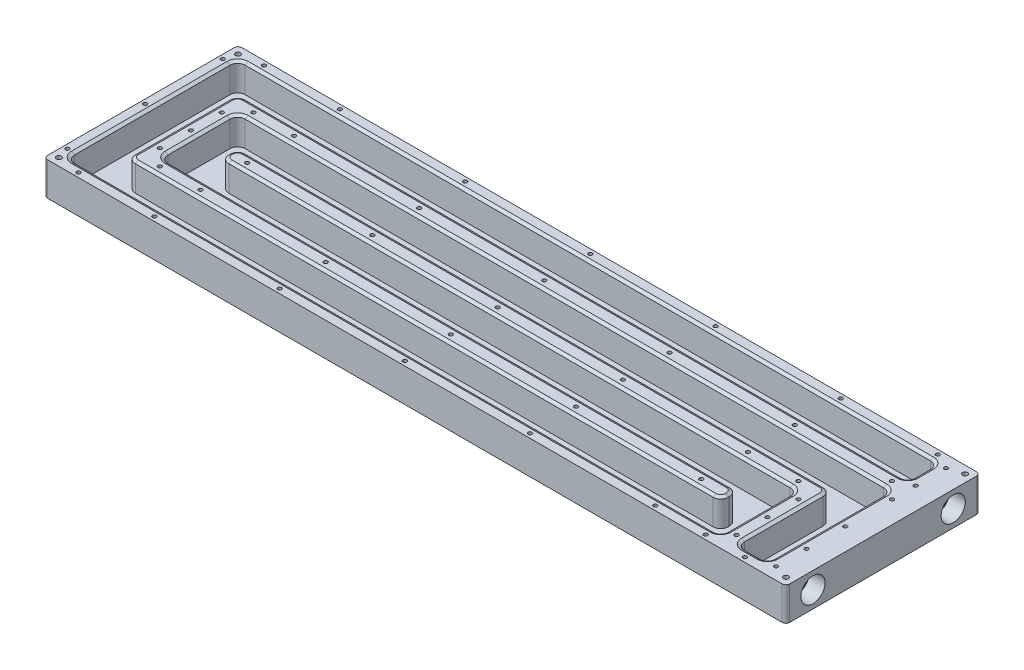
SolidWorks part; units mm, degrees
ref_plane "Front Plane" through (0, 0, 0) normal (0, 0, 1) x (1, 0, 0)
ref_plane "Top Plane" through (0, 0, 0) normal (0, 1, 0) x (1, 0, 0)
ref_plane "Right Plane" through (0, 0, 0) normal (1, 0, 0) x (0, 0, -1)
sketch "Sketch1" plane through (0, 0, 0) normal (0, 1, 0) x (1, 0, 0)
  line L1 (-244.475, 67) -> (244.475, 67)
  line L2 (-244.475, 67) -> (-244.475, -67)
  line L3 (-244.475, -67) -> (244.475, -67)
  line L4 (244.475, 67) -> (244.475, -67)
  line L5 (-244.475, 67) -> (244.475, -67) construction
  line L6 (-244.475, -67) -> (244.475, 67) construction
  point P0 (0, 0)
  dimension "D1" = 134
  dimension "D2" = 488.95
extrude "Boss-Extrude1" add sketch "Sketch1" along normal blind 22
hole_wizard "3/8 NPT Tapped Hole1" positions "Sketch2" profile "Sketch3" size "3/8" standard "ANSI Inch"
sketch "Sketch2" plane through (244.475, 0, 0) normal (1, 0, 0) x (0, 0, -1)
  line L0 (46.2, 11) -> (-46.2, 11) construction
  line L2 (-67, 22) -> (-67, 0) construction
  point P0 (-46.2, 11)
  point P2 (46.2, 11)
  point P8 (0, 11)
  point P12 (-67, 11)
  dimension "D1" = 92.4
sketch "Sketch3" plane through (244.475, 11, 46.2) normal (0, 1, 0) x (0, 0, -1)
  line L0 (0, 0) -> (0, 21.6686)
  line L1 (7.1374, 17.38) -> (0, 21.6686)
  line L2 (-7.1374, 17.38) -> (0, 21.6686) construction
  line L3 (7.1374, 17.38) -> (7.1374, 10.33)
  line L4 (7.1374, 10.33) -> (7.6537, 10.33)
  line L5 (7.6537, 10.33) -> (7.963, 0)
  line L6 (-7.6537, 10.33) -> (-7.963, 0) construction
  line L7 (7.963, 0) -> (0, 0)
  line L8 (0, -6.35) -> (0, 107.95) construction
  line L11 (-7.1374, 10.33) -> (-7.6537, 10.33) construction
  dimension "Tap Drill Dia." = 14.2748
  dimension "Tap Drill Depth" = 17.38
  dimension "Thread Dia." = 15.9261
  dimension "Thread Angle" = 3.43
  dimension "Thread Depth" = 10.33
  dimension "Drill Angle" = 118
cosmetic thread "Hole Thread1" parameters "D1"=10.33, "D2"=17.145
cosmetic thread "Hole Thread2" parameters "D1"=10.33, "D2"=17.145
sketch "Sketch4" plane through (0, 22, 0) normal (0, 1, 0) x (1, 0, 0)
  line L0 (-244.475, 67) -> (-244.475, -67) construction
  line L1 (224.475, 56.2) -> (-236.975, 56.2)
  line L2 (224.475, 56.2) -> (224.475, 36.2)
  line L3 (224.475, 36.2) -> (-236.975, 36.2)
  line L4 (-236.975, 56.2) -> (-236.975, 36.2)
  line L5 (244.475, 67) -> (-244.475, 67) construction
  line L6 (244.475, -67) -> (244.475, 67) construction
  dimension "D1" = 7.5
  dimension "D2" = 10.8
  dimension "D3" = 20
  dimension "D4" = 20
extrude "Cut-Extrude1" cut sketch "Sketch4" against normal blind 18
pattern_linear "LPattern1" count 4 spacing 30.8 along (0, 0, 1) of "Cut-Extrude1"
sketch "Sketch5" plane through (0, 22, 0) normal (0, 1, 0) x (1, 0, 0)
  line L0 (224.475, 25.4) -> (-236.975, 25.4) construction
  line L1 (-236.975, -25.4) -> (-206.175, -25.4)
  line L2 (-236.975, -25.4) -> (-236.975, 25.4)
  line L3 (-236.975, 25.4) -> (-206.175, 25.4)
  line L4 (-206.175, -25.4) -> (-206.175, 25.4)
  dimension "D1" = 30.8
extrude "Boss-Extrude2" add sketch "Sketch5" against normal up to next
sketch "Sketch6" plane through (0, 22, 0) normal (0, 1, 0) x (1, 0, 0)
  line L0 (224.475, -5.4) -> (-206.175, -5.4) construction
  line L1 (224.475, -56.2) -> (193.675, -56.2)
  line L2 (224.475, -56.2) -> (224.475, -5.4)
  line L3 (224.475, -5.4) -> (193.675, -5.4)
  line L4 (193.675, -56.2) -> (193.675, -5.4)
  dimension "D1" = 30.8
extrude "Boss-Extrude3" add sketch "Sketch6" against normal up to next
sketch "Sketch7" plane through (0, 22, 0) normal (0, 1, 0) x (1, 0, 0)
  line L0 (-206.175, 5.4) -> (224.475, 5.4) construction
  line L1 (204.475, 5.4) -> (224.475, 5.4)
  line L2 (204.475, 5.4) -> (204.475, -56.2)
  line L3 (204.475, -56.2) -> (224.475, -56.2)
  line L4 (224.475, 5.4) -> (224.475, -56.2)
  line L5 (-244.475, -67) -> (244.475, -67) construction
  line L6 (193.675, -36.2) -> (193.675, -56.2) construction
  dimension "D1" = 20
  dimension "D2" = 10.8
  dimension "D3" = 10.8
extrude "Cut-Extrude2" cut sketch "Sketch7" against normal blind 18
sketch "Sketch8" plane through (0, 22, 0) normal (0, 1, 0) x (1, 0, 0)
  line L0 (-206.175, -25.4) -> (193.675, -25.4) construction
  line L1 (193.675, -36.2) -> (173.675, -36.2)
  line L2 (193.675, -36.2) -> (193.675, -25.4)
  line L3 (193.675, -25.4) -> (173.675, -25.4)
  line L4 (173.675, -36.2) -> (173.675, -25.4)
  dimension "D1" = 20
extrude "Cut-Extrude3" cut sketch "Sketch8" against normal blind 18
sketch "Sketch9" plane through (0, 22, 0) normal (0, 1, 0) x (1, 0, 0)
  line L0 (-236.975, 36.2) -> (224.475, 36.2) construction
  line L1 (-236.975, -36.2) -> (-216.975, -36.2)
  line L2 (-236.975, -36.2) -> (-236.975, 36.2)
  line L3 (-236.975, 36.2) -> (-216.975, 36.2)
  line L4 (-216.975, -36.2) -> (-216.975, 36.2)
  dimension "D1" = 20
extrude "Cut-Extrude4" cut sketch "Sketch9" against normal blind 18
sketch "Sketch10" plane through (0, 22, 0) normal (0, 1, 0) x (1, 0, 0)
  line L0 (-206.175, 5.4) -> (204.475, 5.4) construction
  line L1 (-206.175, -5.4) -> (-186.175, -5.4)
  line L2 (-206.175, -5.4) -> (-206.175, 5.4)
  line L3 (-206.175, 5.4) -> (-186.175, 5.4)
  line L4 (-186.175, -5.4) -> (-186.175, 5.4)
  dimension "D1" = 20
extrude "Cut-Extrude5" cut sketch "Sketch10" against normal blind 18
fillet "Fillet1" radius 5 18 edges at (193.675, 13, 5.4) (173.675, 13, 25.4) (173.675, 13, 36.2) (193.675, 13, 56.2) (204.475, 13, 56.2) (224.475, 13, 56.2) (204.475, 13, -5.4) (-206.175, 13, -25.4) (224.475, 13, -25.4) (224.475, 13, -36.2) (224.475, 13, -56.2) (-216.975, 13, -36.2) (-216.975, 13, 36.2) (-236.975, 13, 56.2) (-186.175, 13, -5.4) (-186.175, 13, 5.4) (-206.175, 13, 25.4) (-236.975, 13, -56.2)
chamfer "Chamfer1" distance 2 angle 30 36 edges at (3.75, 22, 5.4) (193.675, 22, 30.8) (173.675, 22, 30.8) (-16.25, 22, 25.4) (-206.175, 22, 0) (9.15, 22, -25.4) (224.475, 22, 15.4) (214.475, 22, 56.2) (204.475, 22, 25.4) (9.15, 22, -5.4) (-186.175, 22, 0) (-21.65, 22, 56.2) (-236.975, 22, 0) (-6.25, 22, -56.2) (224.475, 22, -46.2) (3.75, 22, -36.2) (-216.975, 22, 0) (-21.65, 22, 36.2) (-184.7105, 22, 3.9355) (-184.7105, 22, -3.9355) (-215.5105, 22, 34.7355) (-215.5105, 22, -34.7355) (203.0105, 22, -3.9355) (172.2105, 22, 34.7355) (172.2105, 22, 26.8645) (192.2105, 22, 6.8645) (192.2105, 22, 54.7355) (205.9395, 22, 54.7355) (223.0105, 22, 54.7355) (223.0105, 22, -23.9355) (223.0105, 22, -37.6645) (223.0105, 22, -54.7355) (-235.5105, 22, 54.7355) (-204.7105, 22, 23.9355) (-204.7105, 22, -23.9355) (-235.5105, 22, -54.7355)
hole_wizard "Tap Drill for M3x0.5 - Plate Next Mounts" positions "Sketch13" profile "Sketch14" hole size "M3x0.5" standard "ANSI Metric"
sketch "Sketch13" plane through (0, 0, 0) normal (0, -1, 0) x (-1, 0, 0)
  line L0 (191.975, -30.8) -> (191.975, 30.8) construction
  line L3 (244.475, 67) -> (244.475, -67) construction
  point P0 (191.975, -30.8)
  point P2 (191.975, 30.8)
  point P10 (191.975, 0)
  point P13 (244.475, 0)
  dimension "D1" = 61.6
  dimension "D2" = 52.5
sketch "Sketch14" plane through (-191.975, 0, 30.8) normal (1, 0, 0) x (0, 0, -1)
  line L0 (0, 0) -> (0, 10.7511)
  line L1 (0, 10.7511) -> (1.25, 10)
  line L2 (1.25, 10) -> (1.25, 0)
  line L5 (1.25, 0) -> (0, 0)
  line L10 (0, 10.7511) -> (-1.25, 10) construction
  line L11 (0, -6.35) -> (0, 107.95) construction
  dimension "Hole Dia." = 2.5
  dimension "Hole Depth" = 10
  dimension "Drill Angle" = 118
pattern_linear "LPattern2" count 5 spacing 97.75 along (1, 0, 0) of "Tap Drill for M3x0.5 - Plate Next Mounts"
sketch "Sketch15" plane through (0, 22, 0) normal (0, 1, 0) x (1, 0, 0)
  line L0 (-244.475, 67) -> (-244.475, -67) construction
  line L1 (244.475, -67) -> (-244.475, -67)
  line L2 (244.475, -67) -> (244.475, -64)
  line L3 (244.475, -64) -> (-244.475, -64)
  line L4 (-244.475, -67) -> (-244.475, -64)
  dimension "D1" = 3
extrude "Cut-Extrude6" cut sketch "Sketch15" against normal through all
sketch "Sketch16" plane through (0, 22, 0) normal (0, 1, 0) x (1, 0, 0)
  line L0 (-244.475, 67) -> (-244.475, -64) construction
  line L1 (244.475, 67) -> (-244.475, 67)
  line L2 (244.475, 67) -> (244.475, 64)
  line L3 (244.475, 64) -> (-244.475, 64)
  line L4 (-244.475, 67) -> (-244.475, 64)
  dimension "D1" = 3
extrude "Cut-Extrude7" cut sketch "Sketch16" against normal through all
fillet "Fillet2" radius 2.5 4 edges at (-244.475, 11, 64) (-244.475, 11, -64) (244.475, 11, 64) (244.475, 11, -64)
hole_wizard "Tap Drill for M3x0.5 Tap1" positions "Sketch11" profile "Sketch12" hole size "M3x0.5" standard "ANSI Metric"
sketch "Sketch11" plane through (0, 22, 0) normal (0, 1, 0) x (1, 0, 0)
  line L2 (-244.475, 61.5) -> (-244.475, -61.5) construction
  line L3 (-174.475, 34.2) -> (-174.475, 27.4) construction
  line L4 (219.475, 34.2) -> (-211.975, 34.2) construction
  line L5 (-201.175, 27.4) -> (219.475, 27.4) construction
  line L8 (-174.475, -27.4) -> (-174.475, -34.2) construction
  line L9 (168.675, -27.4) -> (-201.175, -27.4) construction
  line L10 (-211.975, -34.2) -> (168.675, -34.2) construction
  line L21 (-174.475, -58.2) -> (-174.475, -64) construction
  line L22 (188.675, -58.2) -> (-231.975, -58.2) construction
  line L23 (241.975, -64) -> (-241.975, -64) construction
  line L26 (-174.475, -3.4) -> (-174.475, 3.4) construction
  line L27 (-181.175, -3.4) -> (188.675, -3.4) construction
  line L28 (199.475, 3.4) -> (-181.175, 3.4) construction
  line L31 (-174.475, 58.2) -> (-174.475, 64) construction
  line L32 (-231.975, 58.2) -> (219.475, 58.2) construction
  line L33 (-241.975, 64) -> (241.975, 64) construction
  point P0 (-174.475, 0)
  point P11 (-174.475, -30.8)
  point P13 (-174.475, -61.1)
  point P15 (-174.475, 30.8)
  point P17 (-174.475, 61.1)
  point P48 (-174.475, -30.8)
  point P49 (-174.475, 30.8)
  point P72 (-174.475, -61.1)
  point P91 (-174.475, 61.1)
  dimension "D2" = 70
sketch "Sketch12" plane through (-174.475, 22, 0) normal (1, 0, 0) x (0, 0, 1)
  line L0 (0, 0) -> (0, 10.7511)
  line L1 (0, 10.7511) -> (1.25, 10)
  line L2 (1.25, 10) -> (1.25, 0)
  line L5 (1.25, 0) -> (0, 0)
  line L10 (0, 10.7511) -> (-1.25, 10) construction
  line L11 (0, -6.35) -> (0, 107.95) construction
  dimension "Hole Dia." = 2.5
  dimension "Hole Depth" = 10
  dimension "Drill Angle" = 118
sketch "Sketch17" [suppressed] plane through (0, 0, 0) normal (0, -1, 0) x (-1, 0, 0)
  line L0 (-199.075, -30.7906) -> (-199.025, -30.8) construction
  line L1 (-202.475, -27.6993) -> (-195.675, -27.6993) construction
  line L2 (-202.475, -51.2) -> (-202.475, 0.4) construction
  line L3 (-195.675, -10.4) -> (-195.675, -51.2) construction
  point P0 (-199.075, -30.7906)
  point P10 (-199.075, -27.6993)
pattern_linear "LPattern3" count 5 spacing 82.5 along (1, 0, 0) of "Tap Drill for M3x0.5 Tap1"
hole_wizard "Tap Drill for M3x0.5 Tap3" positions "Sketch18" profile "Sketch19" hole size "M3x0.5" standard "ANSI Metric"
sketch "Sketch18" plane through (0, 22, 0) normal (0, 1, 0) x (1, 0, 0)
  line L0 (188.675, -58.2) -> (188.675, -64) construction
  line L1 (241.975, -64) -> (-241.975, -64) construction
  line L4 (202.475, -51.2) -> (195.675, -51.2) construction
  line L7 (202.475, -30.8) -> (195.675, -30.8) construction
  line L8 (202.475, -51.2) -> (202.475, 0.4) construction
  line L9 (195.675, -10.4) -> (195.675, -51.2) construction
  line L12 (195.675, -10.4) -> (202.475, -10.4) construction
  line L15 (188.675, -3.4) -> (188.675, 3.4) construction
  line L16 (199.475, 3.4) -> (-181.175, 3.4) construction
  point P0 (199.075, -30.8)
  point P2 (188.675, 0)
  point P4 (199.075, -10.4)
  point P6 (199.075, -51.2)
  point P8 (188.675, -61.1)
  point P51 (199.075, -10.4)
  point P52 (199.075, -30.8)
  point P53 (199.075, -51.2)
  point P54 (188.675, -61.1)
sketch "Sketch19" plane through (199.075, 22, 30.8) normal (1, 0, 0) x (0, 0, 1)
  line L0 (0, 0) -> (0, 10.7511)
  line L1 (0, 10.7511) -> (1.25, 10)
  line L2 (1.25, 10) -> (1.25, 0)
  line L5 (1.25, 0) -> (0, 0)
  line L10 (0, 10.7511) -> (-1.25, 10) construction
  line L11 (0, -6.35) -> (0, 107.95) construction
  dimension "Hole Dia." = 2.5
  dimension "Hole Depth" = 10
  dimension "Drill Angle" = 118
hole_wizard "Tap Drill for M3x0.5 Tap4" positions "Sketch20" profile "Sketch21" hole size "M3x0.5" standard "ANSI Metric"
sketch "Sketch20" plane through (0, 22, 0) normal (0, 1, 0) x (1, 0, 0)
  line L0 (229.975, -56) -> (229.975, 56) construction
  line L2 (226.475, 20.4) -> (226.475, -51.2) construction
  line L3 (219.475, 27.4) -> (219.475, 34.2) construction
  line L4 (-201.175, 27.4) -> (219.475, 27.4) construction
  line L5 (219.475, 34.2) -> (-211.975, 34.2) construction
  line L8 (219.475, 58.2) -> (219.475, 64) construction
  line L9 (-231.975, 58.2) -> (219.475, 58.2) construction
  line L10 (-241.975, 64) -> (241.975, 64) construction
  line L13 (214.475, -58.2) -> (214.475, -64) construction
  line L14 (219.475, -58.2) -> (209.475, -58.2) construction
  line L15 (241.975, -64) -> (-241.975, -64) construction
  line L18 (199.075, -10.4) -> (229.975, -10.4) construction
  line L20 (229.975, -56) -> (229.975, -36) construction
  point P0 (219.475, 61.1)
  point P2 (219.475, 30.8)
  point P4 (229.975, 36)
  point P6 (229.975, 56)
  point P8 (229.975, 20.4)
  point P10 (229.975, -10.4)
  point P12 (229.975, -36)
  point P14 (229.975, -56)
  point P16 (214.475, -61.1)
  point P52 (214.475, -61.1)
  point P53 (214.475, -58.2)
  point P54 (219.475, 30.8)
  point P55 (219.475, 61.1)
  dimension "D1" = 3.5
  dimension "D2" = 20
  dimension "D3" = 20
  dimension "D4" = 8
  dimension "D5" = 8
sketch "Sketch21" plane through (219.475, 22, -61.1) normal (1, 0, 0) x (0, 0, 1)
  line L0 (0, 0) -> (0, 10.7511)
  line L1 (0, 10.7511) -> (1.25, 10)
  line L2 (1.25, 10) -> (1.25, 0)
  line L5 (1.25, 0) -> (0, 0)
  line L10 (0, 10.7511) -> (-1.25, 10) construction
  line L11 (0, -6.35) -> (0, 107.95) construction
  dimension "Hole Dia." = 2.5
  dimension "Hole Depth" = 10
  dimension "Drill Angle" = 118
hole_wizard "Tap Drill for M4x0.7 Tap1" positions "Sketch22" profile "Sketch23" hole size "M4x0.7" standard "ANSI Metric"
sketch "Sketch22" plane through (0, 22, 0) normal (0, 1, 0) x (1, 0, 0)
  line L0 (-239.475, -59) -> (-239.475, 59) construction
  line L1 (-239.475, 59) -> (239.475, 59) construction
  line L2 (239.475, 59) -> (239.475, -59) construction
  line L3 (239.475, -59) -> (-239.475, -59) construction
  line L6 (241.975, -64) -> (-241.975, -64) construction
  line L7 (-244.475, 61.5) -> (-244.475, -61.5) construction
  line L8 (-241.975, 64) -> (241.975, 64) construction
  line L9 (244.475, -61.5) -> (244.475, 61.5) construction
  point P0 (239.475, -59)
  point P2 (239.475, 59)
  point P4 (-239.475, 59)
  point P6 (-239.475, -59)
  dimension "D1" = 5
  dimension "D2" = 5
  dimension "D3" = 5
  dimension "D4" = 5
sketch "Sketch23" plane through (239.475, 22, 59) normal (1, 0, 0) x (0, 0, 1)
  line L0 (0, 0) -> (0, 18.3714)
  line L1 (0, 18.3714) -> (1.65, 17.38)
  line L2 (1.65, 17.38) -> (1.65, 0)
  line L5 (1.65, 0) -> (0, 0)
  line L10 (0, 18.3714) -> (-1.65, 17.38) construction
  line L11 (0, -6.35) -> (0, 107.95) construction
  dimension "Hole Dia." = 3.3
  dimension "Hole Depth" = 17.38
  dimension "Drill Angle" = 118
hole_wizard "Tap Drill for M3x0.5 Tap5" positions "Sketch24" profile "Sketch25" hole size "M3x0.5" standard "ANSI Metric"
sketch "Sketch24" plane through (0, 22, 0) normal (0, 1, 0) x (1, 0, 0)
  line L0 (-208.175, -20.4) -> (-214.975, -20.4) construction
  line L1 (-214.975, 31.2) -> (-214.975, -31.2) construction
  line L4 (-208.175, 0) -> (-214.975, 0) construction
  line L5 (-208.175, -20.4) -> (-208.175, 20.4) construction
  line L8 (-208.175, 20.4) -> (-214.975, 20.4) construction
  line L11 (-201.175, 27.4) -> (-201.175, 34.2) construction
  line L12 (219.475, 34.2) -> (-211.975, 34.2) construction
  line L15 (-201.175, -27.4) -> (-201.175, -34.2) construction
  line L16 (-211.975, -34.2) -> (168.675, -34.2) construction
  line L19 (-238.975, -51.2) -> (-244.475, -51.2) construction
  line L20 (-244.475, 61.5) -> (-244.475, -61.5) construction
  line L23 (-238.975, 0) -> (-244.475, 0) construction
  line L24 (-238.975, -51.2) -> (-238.975, 51.2) construction
  line L27 (-238.975, 51.2) -> (-244.475, 51.2) construction
  line L30 (-224.475, 58.2) -> (-224.475, 64) construction
  line L31 (-231.975, 58.2) -> (219.475, 58.2) construction
  line L32 (-241.975, 64) -> (241.975, 64) construction
  line L35 (-224.475, -58.2) -> (-224.475, -64) construction
  line L36 (188.675, -58.2) -> (-231.975, -58.2) construction
  line L37 (241.975, -64) -> (-241.975, -64) construction
  arc A0 (-201.175, 27.4) -> (-208.175, 20.4) centre (-201.175, 20.4) ccw construction
  point P0 (-211.575, 0)
  point P2 (-211.575, -20.4)
  point P4 (-211.575, 20.4)
  point P6 (-201.175, 30.8)
  point P8 (-201.175, -30.8)
  point P10 (-224.475, -61.1)
  point P12 (-241.725, -51.2)
  point P14 (-241.725, 0)
  point P16 (-241.725, 51.2)
  point P18 (-224.475, 61.1)
  point P100 (-241.725, -51.2)
  point P101 (-224.475, -61.1)
  point P102 (-201.175, -30.8)
  point P103 (-211.575, -20.4)
  point P104 (-211.575, 0)
  point P105 (-241.725, 0)
  point P106 (-211.575, 20.4)
  point P107 (-201.175, 30.8)
  point P108 (-224.475, 61.1)
  point P109 (-241.725, 51.2)
  dimension "D1" = 20
  dimension "D2" = 20
sketch "Sketch25" plane through (-211.575, 22, 0) normal (1, 0, 0) x (0, 0, 1)
  line L0 (0, 0) -> (0, 10.7511)
  line L1 (0, 10.7511) -> (1.25, 10)
  line L2 (1.25, 10) -> (1.25, 0)
  line L5 (1.25, 0) -> (0, 0)
  line L10 (0, 10.7511) -> (-1.25, 10) construction
  line L11 (0, -6.35) -> (0, 107.95) construction
  dimension "Hole Dia." = 2.5
  dimension "Hole Depth" = 10
  dimension "Drill Angle" = 118
